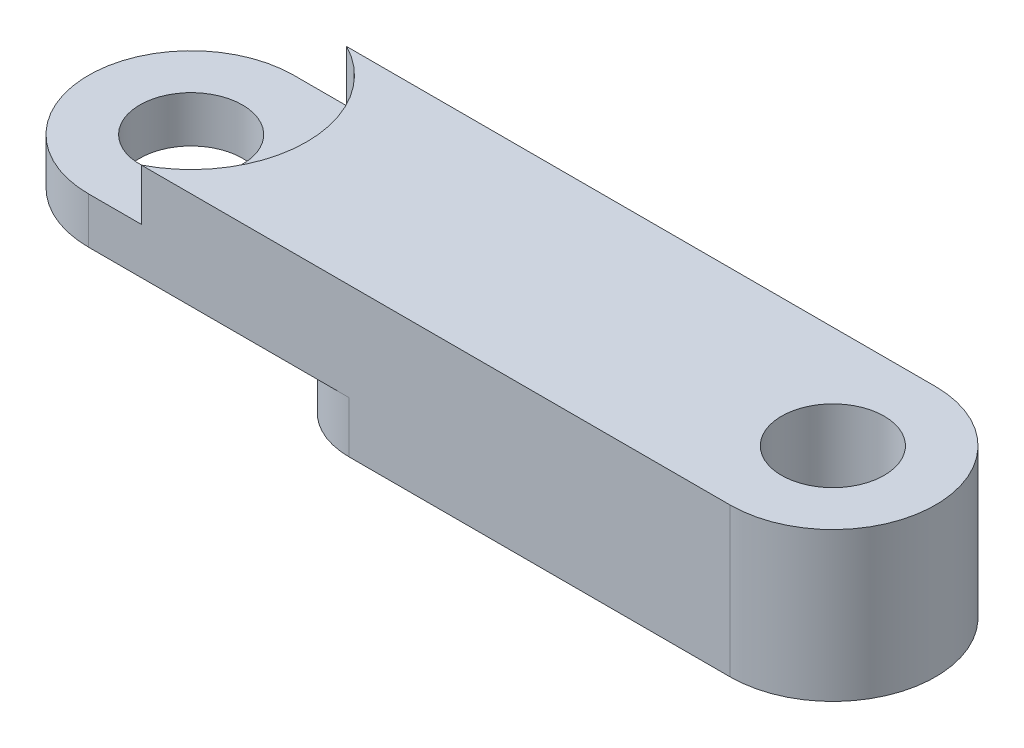
SolidWorks part; units mm, degrees
ref_plane "Front Plane" through (0, 0, 0) normal (0, 0, 1) x (1, 0, 0)
ref_plane "Top Plane" through (0, 0, 0) normal (0, 1, 0) x (1, 0, 0)
ref_plane "Right Plane" through (0, 0, 0) normal (1, 0, 0) x (0, 0, -1)
sketch "Sketch1" plane through (0, 0, 0) normal (0, 1, 0) x (1, 0, 0)
  line L0 (-125, 0) -> (0, 0) construction
  line L1 (0, 0) -> (125, 0) construction
  line L2 (-125, 40) -> (125, 40)
  line L3 (-125, -40) -> (125, -40)
  circle A0 centre (-125, 0) radius 20
  circle A1 centre (125, 0) radius 20
  arc A2 (-125, 40) -> (-125, -40) centre (-125, 0) ccw
  arc A3 (125, -40) -> (125, 40) centre (125, 0) ccw
  dimension "D3" = 40
  dimension "D4" = 40
  dimension "D5" = 80
  dimension "D6" = 80
  dimension "D1" = 125
  dimension "D2" = 125
extrude "Boss-Extrude1" add sketch "Sketch1" along normal blind 58
sketch "Sketch3" plane through (0, 58, 0) normal (0, 1, 0) x (1, 0, 0)
  circle A0 centre (-125, 0) radius 45
  dimension "D1" = 90
extrude "Cut-Extrude2" cut sketch "Sketch3" against normal blind 20
sketch "Sketch4" plane through (0, 0, 0) normal (0, -1, 0) x (1, 0, 0)
  circle A0 centre (-125, 0) radius 45
  dimension "D1" = 90
extrude "Cut-Extrude3" cut sketch "Sketch4" against normal blind 20
sketch "Sketch6" plane through (0, 0, 0) normal (0, -1, 0) x (1, 0, 0)
  line L4 (165, 0) -> (-125, 0) construction
  line L5 (-104.3845, 40) -> (125, 40) construction
  line L6 (-196.4982, -40) -> (-53.5018, -40)
  line L7 (-196.4982, -40) -> (-196.4982, 40)
  line L8 (-196.4982, 40) -> (-53.5018, 40)
  line L9 (-53.5018, -40) -> (-53.5018, 40)
  line L10 (-196.4982, -40) -> (-53.5018, 40) construction
  line L11 (-196.4982, 40) -> (-53.5018, -40) construction
  arc A0 (125, -40) -> (125, 40) centre (125, 0) ccw construction
extrude "Cut-Extrude6" cut sketch "Sketch6" against normal up to surface (20 mm away) up to face at (-125, 20, -20)
fillet "Fillet1" radius 30 2 edges at (-53.5018, 10, 40) (-53.5018, 10, -40)
